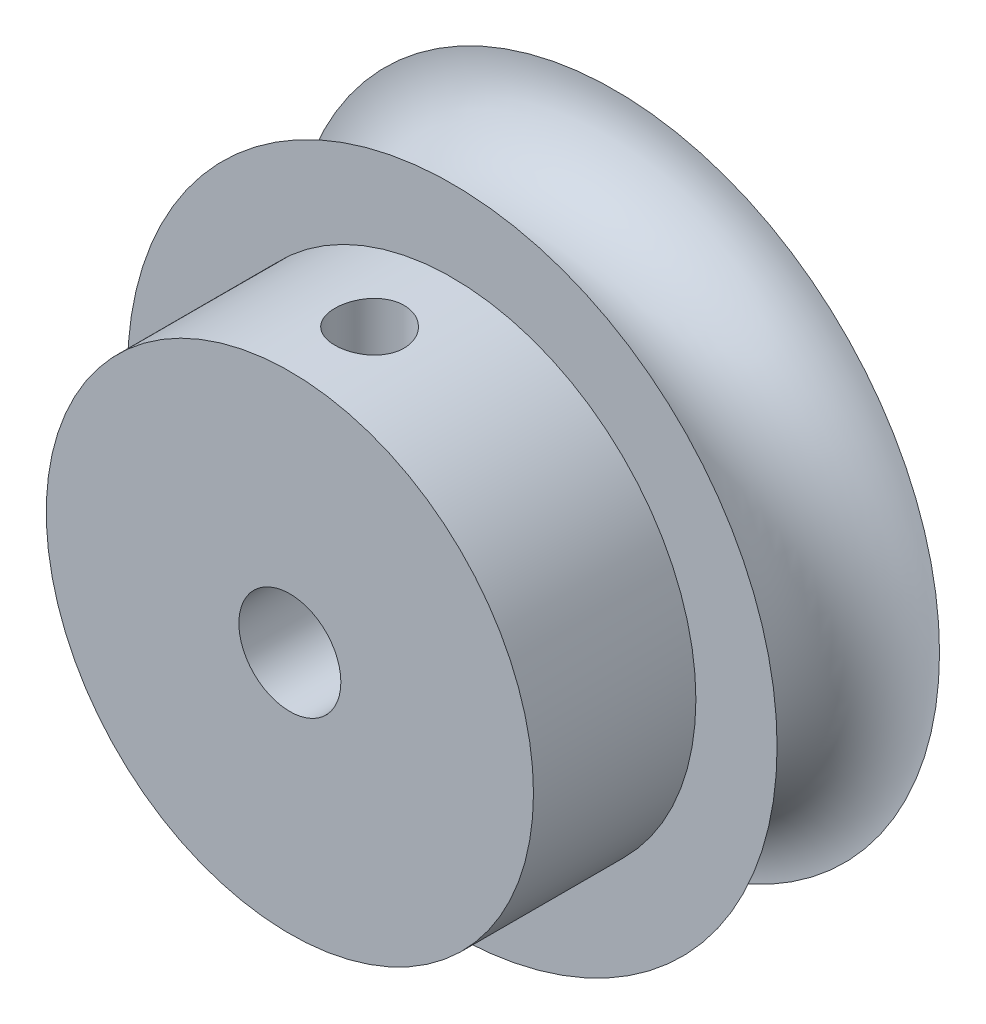
SolidWorks part; units mm, degrees
ref_plane "Front Plane" through (0, 0, 0) normal (0, 0, 1) x (1, 0, 0)
ref_plane "Top Plane" through (0, 0, 0) normal (0, 1, 0) x (1, 0, 0)
ref_plane "Right Plane" through (0, 0, 0) normal (1, 0, 0) x (0, 0, -1)
sketch "Sketch1" plane through (0, 0, 0) normal (0, 0, 1) x (1, 0, 0)
  circle A0 centre (0, 0) radius 12.7
extrude "Boss-Extrude1" add sketch "Sketch1" along normal blind 6.35
sketch "Sketch2" plane through (0, 0, 6.35) normal (0, 0, 1) x (1, 0, 0)
  circle A0 centre (0, 0) radius 9.525
extrude "Boss-Extrude2" add sketch "Sketch2" along normal blind 6.35
sketch "Sketch3" plane through (0, 0, 12.7) normal (0, 0, 1) x (1, 0, 0)
  circle A0 centre (0, 0) radius 1.9939
extrude "Cut-Extrude1" cut sketch "Sketch3" against normal blind 12.7
sketch "Sketch4" plane through (0, 0, 0) normal (0, 1, 0) x (1, 0, 0)
  line L0 (12.7, 0) -> (12.7, -6.35)
  line L1 (0, 3.5759) -> (0, -14.3879) construction
  arc A0 (12.7, 0) -> (12.7, -6.35) centre (12.7, -3.175) ccw
revolve "Cut-Revolve1" cut sketch "Sketch4" angle 360 about L1
sketch "Sketch5" plane through (0, 0, 0) normal (0, 1, 0) x (1, 0, 0)
  circle A0 centre (0, -9.525) radius 1.8986
hole_wizard "#6-32 Tapped Hole1" positions "3DSketch1" profile "Sketch6" tap size "#6-32" standard "Ansi Inch"
sketch3d "3DSketch1"
  point P0 (0, 9.525, 9.584)
  point P10 (0, 0, 0)
sketch "Sketch6" plane through (0, 9.525, 9.584) normal (0, 0, 1) x (-1, 0, 0)
  line L0 (0, 0) -> (0, 10.3367)
  line L1 (0, 10.3367) -> (1.3525, 9.524)
  line L2 (1.3525, 9.524) -> (1.3525, 0)
  line L5 (1.3525, 0) -> (0, 0)
  line L10 (0, 10.3367) -> (-1.3526, 9.524) construction
  line L11 (0, -6.35) -> (0, 107.95) construction
  dimension "Tap Drill Dia." = 2.7051
  dimension "Tap Drill Depth" = 9.524
  dimension "Drill Angle" = 118
cosmetic thread "Hole Thread1" parameters "D1"=6.6525, "D2"=3.5052
